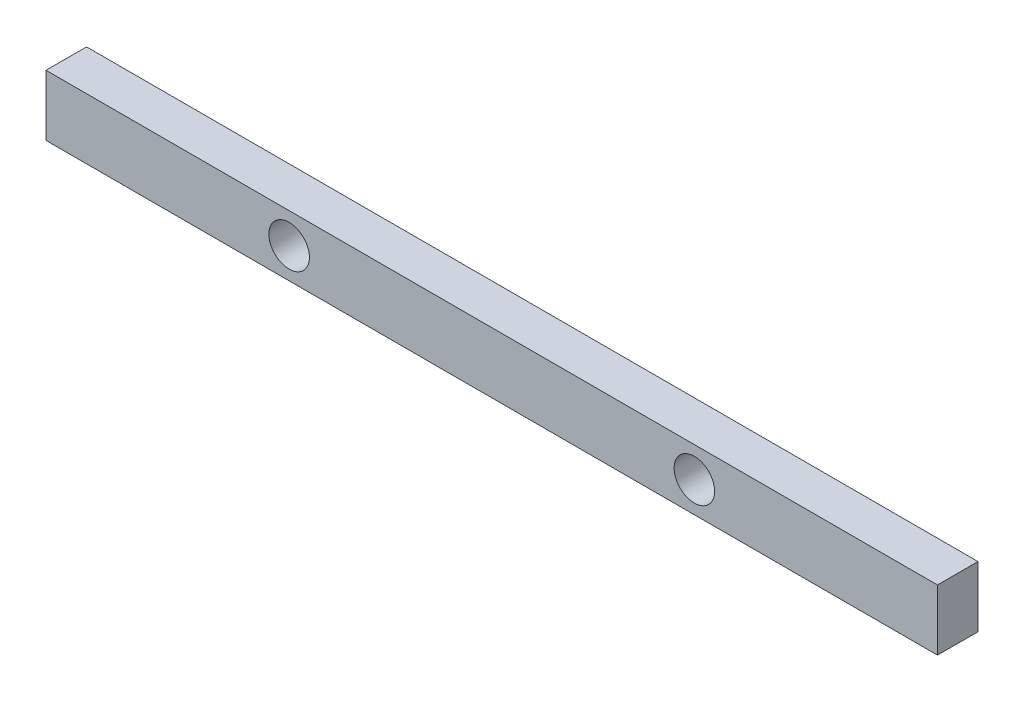
SolidWorks part; units mm, degrees
ref_plane "Front" through (0, 0, 0) normal (0, 0, 1) x (1, 0, 0)
ref_plane "Top" through (0, 0, 0) normal (0, 1, 0) x (1, 0, 0)
ref_plane "Right" through (0, 0, 0) normal (1, 0, 0) x (0, 0, -1)
sketch "草图1" plane through (0, 0, 0) normal (0, 0, 1) x (1, 0, 0)
  line L0 (0, 0) -> (0, 5.624) construction
  line L1 (-22, 1.5) -> (22, 1.5)
  line L2 (-22, 1.5) -> (-22, -1.5)
  line L3 (-22, -1.5) -> (22, -1.5)
  line L4 (22, 1.5) -> (22, -1.5)
  line L5 (-22, 1.5) -> (22, -1.5) construction
  line L6 (-22, -1.5) -> (22, 1.5) construction
  circle A0 centre (-10, 0) radius 1
  circle A1 centre (10, 0) radius 1
  point P0 (0, 0)
  dimension "D3" = 20
  dimension "D4" = 2
  dimension "D1" = 3
  dimension "D2" = 44
extrude "凸台-拉伸1" add sketch "草图1" along normal blind 2
